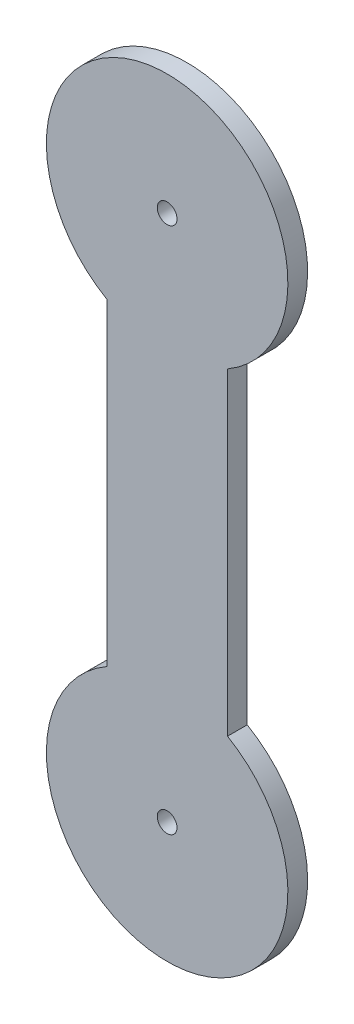
SolidWorks part; units mm, degrees
ref_plane "Front Plane" through (0, 0, 0) normal (0, 0, 1) x (1, 0, 0)
ref_plane "Top Plane" through (0, 0, 0) normal (0, 1, 0) x (1, 0, 0)
ref_plane "Right Plane" through (0, 0, 0) normal (1, 0, 0) x (0, 0, -1)
sketch "Sketch1" plane through (0, 0, 0) normal (0, 0, 1) x (1, 0, 0)
  line L1 (0, 0) -> (38.1, 0)
  line L2 (0, 0) -> (0, 166.37)
  line L3 (0, 166.37) -> (38.1, 166.37)
  line L4 (38.1, 0) -> (38.1, 166.37)
  circle A0 centre (19.05, 166.37) radius 3.1115
  circle A1 centre (19.05, 0) radius 3.1115
  circle A2 centre (19.05, 166.37) radius 38.1
  circle A3 centre (19.05, 0) radius 38.1
  dimension "D3" = 6.223
  dimension "D4" = 6.223
  dimension "D5" = 76.2
  dimension "D6" = 76.2
  dimension "D1" = 38.1
  dimension "D2" = 166.37
extrude "Boss-Extrude1" add sketch "Sketch1" along normal blind 6.223 contours L2 A2 L4 L3 A0 | L4 A2 L2 L3 A0 | A3 L4 A2 L2 | L4 A3 L2 L1 A1 | L2 A3 L4 L1 A1
